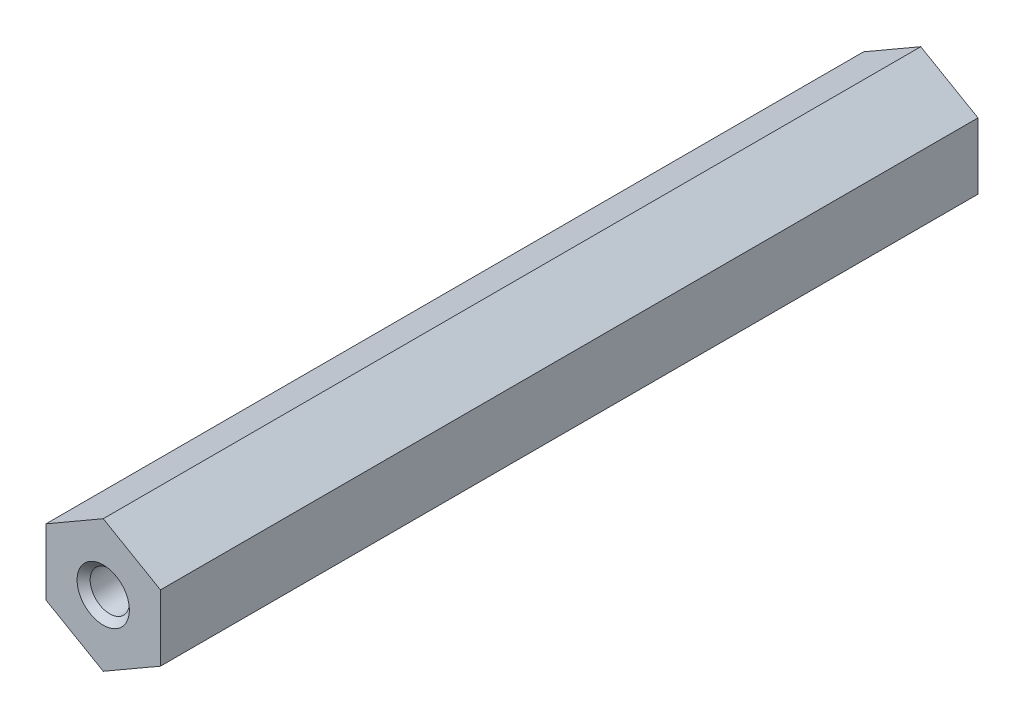
SolidWorks part; units mm, degrees
ref_plane "Спереди" through (0, 0, 0) normal (0, 0, 1) x (1, 0, 0)
ref_plane "Сверху" through (0, 0, 0) normal (0, 1, 0) x (1, 0, 0)
ref_plane "Справа" through (0, 0, 0) normal (1, 0, 0) x (0, 0, -1)
sketch "Эскиз1" plane through (0, 0, 0) normal (0, 0, 1) x (1, 0, 0)
  line L1 (0, 4.0415) -> (-3.5, 2.0207)
  line L2 (-3.5, 2.0207) -> (-3.5, -2.0207)
  line L3 (-3.5, -2.0207) -> (0, -4.0415)
  line L4 (0, -4.0415) -> (3.5, -2.0207)
  line L5 (3.5, -2.0207) -> (3.5, 2.0207)
  line L6 (3.5, 2.0207) -> (0, 4.0415)
  circle A0 centre (0, 0) radius 3.5 construction
  dimension "D1" = 7
extrude "Вытянуть1" add sketch "Эскиз1" along normal blind 50
sketch "Эскиз2" plane through (0, 0, 50) normal (0, 0, 1) x (1, 0, 0)
  circle A0 centre (0, 0) radius 1.2
  dimension "D1" = 2.4
extrude "Вырез-Вытянуть1" cut sketch "Эскиз2" against normal blind 12
cosmetic thread "Условное изображение резьбы1" parameters "D1"=8, "D2"=3
chamfer "Фаска1" distance 1.2 angle 30 1 edges at (1.2, 0, 38)
sketch "Эскиз3" plane through (0, 0, 0) normal (0, 0, -1) x (-1, 0, 0)
  circle A0 centre (0, 0) radius 2.1
  dimension "D1" = 4.2
extrude "Вырез-Вытянуть2" cut sketch "Эскиз3" against normal blind 12
cosmetic thread "Условное изображение резьбы2" parameters "D1"=8, "D2"=5
chamfer "Фаска2" distance 2.1 angle 30 1 edges at (-2.1, 0, 12)
chamfer "Фаска3" distance 0.4 angle 45 2 edges at (1.2, 0, 50) (-2.1, 0, 0)
